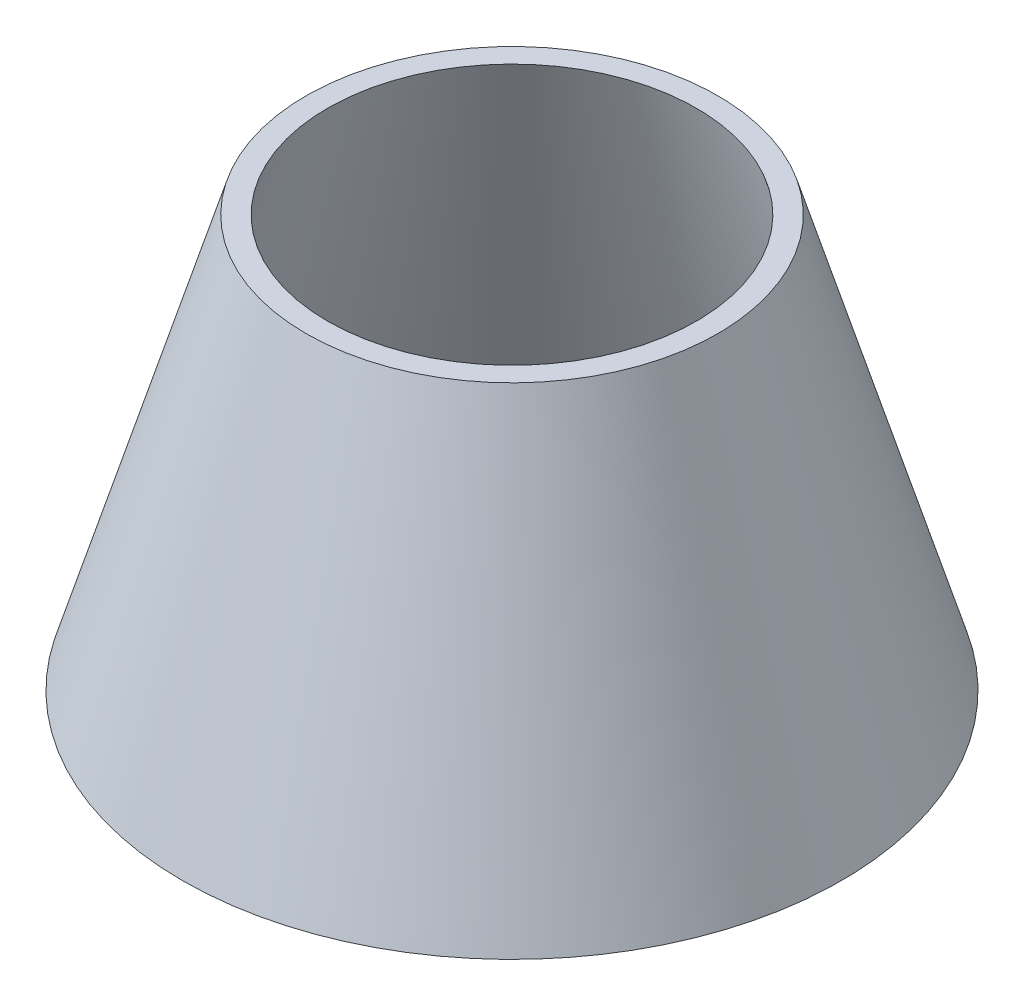
SolidWorks part; units mm, degrees
ref_plane "Front" through (0, 0, 0) normal (0, 0, 1) x (1, 0, 0)
ref_plane "Top" through (0, 0, 0) normal (0, 1, 0) x (1, 0, 0)
ref_plane "Right" through (0, 0, 0) normal (1, 0, 0) x (0, 0, -1)
sketch "Sketch1" plane through (0, 0, 0) normal (0, 1, 0) x (1, 0, 0)
  circle A0 centre (0, 0) radius 50.8
  dimension "D1" = 101.6
ref_plane "Plane1" through (0, 63.5, 0) normal (0, 1, 0) x (1, 0, 0)
sketch "Sketch2" plane through (0, 63.5, 0) normal (0, 1, 0) x (1, 0, 0)
  circle A0 centre (0, 0) radius 31.75
  dimension "D1" = 63.5
loft "Loft1" add profiles "Sketch2", "Sketch1"
shell "Shell1" thickness 3.175
